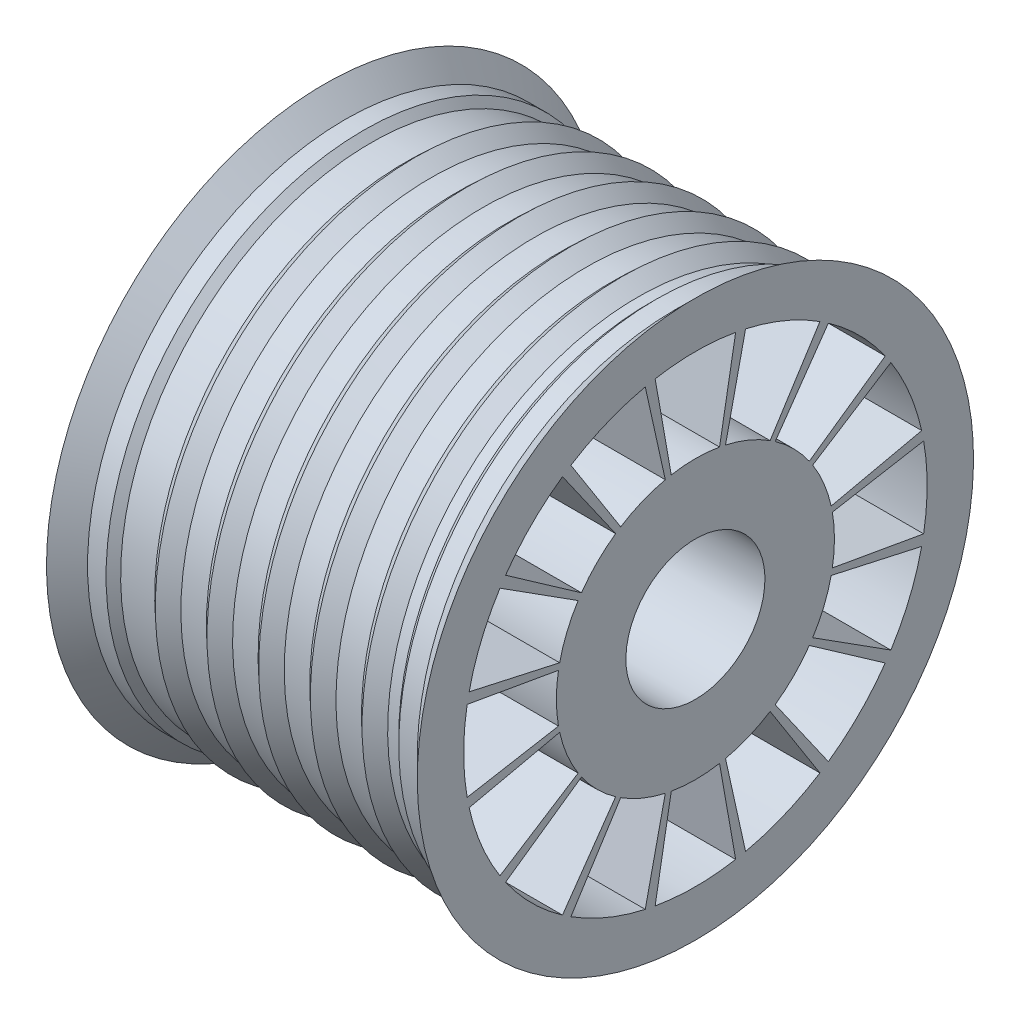
SolidWorks part; units mm, degrees
ref_plane "Front Plane" through (0, 0, 0) normal (0, 0, 1) x (1, 0, 0)
ref_plane "Top Plane" through (0, 0, 0) normal (0, 1, 0) x (1, 0, 0)
ref_plane "Right Plane" through (0, 0, 0) normal (1, 0, 0) x (0, 0, -1)
sketch "Sketch2" plane through (0, 0, 0) normal (0, 0, 1) x (1, 0, 0)
  line L1 (-20, 0) -> (-20, 30)
  line L2 (-20, 30) -> (-17.7857, 27.7857)
  line L3 (-17.7857, 27.7857) -> (-15.7857, 27.7857)
  line L4 (-15.7857, 27.7857) -> (-15, 27)
  line L6 (15, 27) -> (15.7857, 27.7857)
  line L7 (15.7857, 27.7857) -> (17.7857, 27.7857)
  line L8 (17.7857, 27.7857) -> (20, 30)
  line L9 (20, 30) -> (20, 0)
  line L11 (-20, 0) -> (20, 0) construction
  line L12 (20, 0) -> (-20, 0)
  line L13 (-15, 27) -> (-11.3276, 27)
  line L14 (-11.3276, 27) -> (-10.2349, 28.0276)
  line L15 (-10.2349, 28.0276) -> (-8.5024, 27)
  line L16 (-5.7516, 27) -> (-4.6589, 28.0276)
  line L17 (-4.6589, 28.0276) -> (-2.9265, 27)
  line L18 (-0.1757, 27) -> (0.917, 28.0276)
  line L19 (0.917, 28.0276) -> (2.6494, 27)
  line L20 (5.4002, 27) -> (6.4929, 28.0276)
  line L21 (6.4929, 28.0276) -> (8.2253, 27)
  line L22 (10.9761, 27) -> (12.0688, 28.0276)
  line L23 (12.0688, 28.0276) -> (13.8013, 27)
  line L24 (-8.5024, 27) -> (-5.7516, 27)
  line L25 (-2.9265, 27) -> (-0.1757, 27)
  line L26 (2.6494, 27) -> (5.4002, 27)
  line L27 (8.2253, 27) -> (10.9761, 27)
  line L28 (13.8013, 27) -> (15, 27)
  point P0 (-15, 27)
  point P2 (0, 0)
  dimension "D1" = 40
  dimension "D2" = 30
  dimension "D3" = 30
  dimension "D4" = 135
  dimension "D5" = 2
  dimension "D6" = 5
  dimension "D7" = 1.5
revolve "Revolve1" add sketch "Sketch2" angle 360 about L11
sketch "Sketch3" plane through (-20, 0, 0) normal (-1, 0, 0) x (0, 0, 1)
  circle A0 centre (0, 0) radius 7.5
  dimension "D1" = 15
extrude "Cut-Extrude1" cut sketch "Sketch3" against normal through all
sketch "Sketch4" plane through (-20, 0, 0) normal (-1, 0, 0) x (0, 0, 1)
  line L0 (0, 0) -> (0, 36.0171) construction
  line L1 (-2.6047, 14.7721) -> (-4.3412, 24.6202)
  line L2 (2.6047, 14.7721) -> (4.3412, 24.6202)
  line L3 (-2.6047, 14.7721) -> (0, 0) construction
  line L4 (2.6047, 14.7721) -> (0, 0) construction
  arc A0 (2.6047, 14.7721) -> (-2.6047, 14.7721) centre (0, 0) ccw
  arc A1 (4.3412, 24.6202) -> (-4.3412, 24.6202) centre (0, 0) ccw
  dimension "D1" = 30
  dimension "D2" = 50
  dimension "D3" = 10
  dimension "D4" = 10
extrude "Cut-Extrude4" cut sketch "Sketch4" against normal blind 10
pattern_circular "CirPattern1" count 16 over 360 about axis through (0, 0, 0) along (1, 0, 0) of "Cut-Extrude4"
mirror "Mirror1" about plane through (0, 0, 0) normal (1, 0, 0) of "Cut-Extrude4"
mirror "Mirror2" about plane through (0, 0, 0) normal (1, 0, 0) of "CirPattern1"
